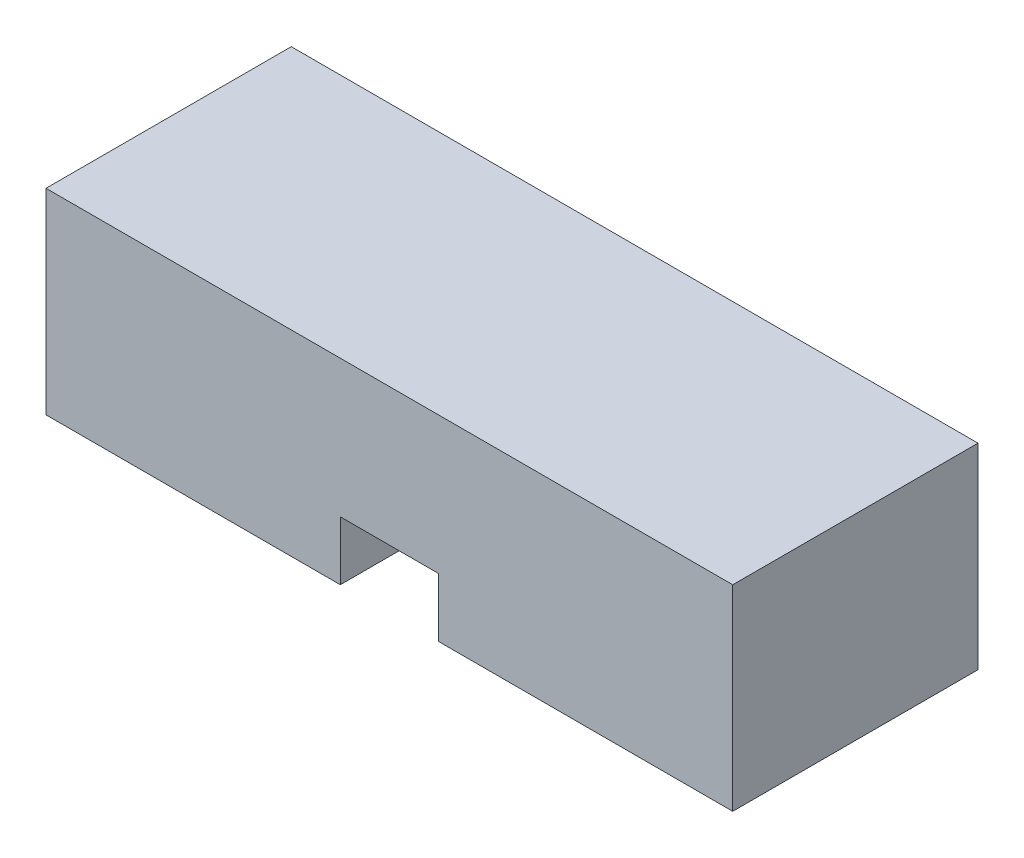
SolidWorks part; units mm, degrees
ref_plane "Front Plane" through (0, 0, 0) normal (0, 0, 1) x (1, 0, 0)
ref_plane "Top Plane" through (0, 0, 0) normal (0, 1, 0) x (1, 0, 0)
ref_plane "Right Plane" through (0, 0, 0) normal (1, 0, 0) x (0, 0, -1)
sketch "Sketch1" plane through (0, 0, 0) normal (0, 1, 0) x (1, 0, 0)
  line L1 (-35, 12.5) -> (35, 12.5)
  line L2 (-35, 12.5) -> (-35, -12.5)
  line L3 (-35, -12.5) -> (35, -12.5)
  line L4 (35, 12.5) -> (35, -12.5)
  line L5 (-35, 12.5) -> (35, -12.5) construction
  line L6 (-35, -12.5) -> (35, 12.5) construction
  point P0 (0, 0)
  dimension "D1" = 70
  dimension "D2" = 25
extrude "Boss-Extrude1" add sketch "Sketch1" against normal blind 20
sketch "Sketch2" plane through (0, -20, 0) normal (0, -1, 0) x (1, 0, 0)
  line L0 (-10.95, -2.1988) -> (0, -2.1988) construction
  line L1 (0, -13.7501) -> (0, 13.7501) construction
  line L2 (10.95, -2.1988) -> (0, -2.1988) construction
  line L3 (-35, 12.5) -> (35, 12.5) construction
  circle A0 centre (-10.95, -2.1988) radius 7.95
  circle A1 centre (10.95, -2.1988) radius 7.95
  dimension "D1" = 15.9
  dimension "D2" = 21.9
  dimension "D3" = 14.6988
sketch "Sketch3" plane through (0, -20, 0) normal (0, -1, 0) x (1, 0, 0)
  line L0 (0, -13.7501) -> (0, 13.7501) construction
  line L1 (-5, -12.5) -> (5, -12.5)
  line L2 (-5, -12.5) -> (-5, 12.5)
  line L3 (-5, 12.5) -> (5, 12.5)
  line L4 (5, -12.5) -> (5, 12.5)
  line L5 (-5, -12.5) -> (5, 12.5) construction
  line L6 (-5, 12.5) -> (5, -12.5) construction
  line L7 (-35, 12.5) -> (35, 12.5) construction
  line L8 (35, -12.5) -> (-35, -12.5) construction
  point P0 (0, 0)
  dimension "D1" = 10
extrude "Cut-Extrude1" cut sketch "Sketch2" against normal blind 7
extrude "Cut-Extrude2" cut sketch "Sketch3" against normal blind 4
sketch "Sketch7" plane through (0, -20, 0) normal (0, -1, 0) x (1, 0, 0)
  line L0 (5, 12.5) -> (-5, 12.5) construction
  line L1 (-5, 3.5) -> (5, 3.5)
  line L2 (-5, 3.5) -> (-5, 12.5)
  line L3 (-5, 12.5) -> (5, 12.5)
  line L4 (5, 3.5) -> (5, 12.5)
  line L5 (-5, 3.5) -> (5, 12.5) construction
  line L6 (-5, 12.5) -> (5, 3.5) construction
  line L7 (0, -11) -> (0, 11) construction
  line L8 (-5, -12.5) -> (5, -12.5) construction
  point P0 (0, 8)
  dimension "D1" = 10
  dimension "D2" = 16
extrude "Cut-Extrude3" cut sketch "Sketch7" against normal blind 6
fillet "Fillet1" radius 3.2 2 edges at (5, -15, 3.5) (-5, -15, 3.5)
